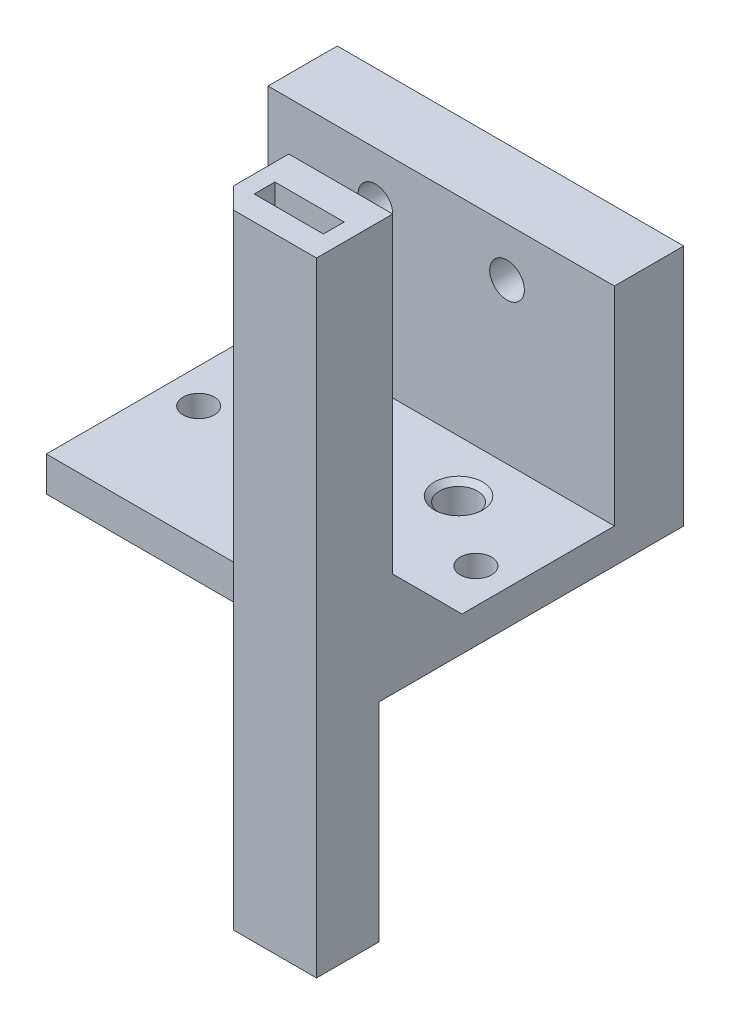
SolidWorks part; units mm, degrees
material "PET"
ref_plane "Front Plane" through (0, 0, 0) normal (0, 0, 1) x (1, 0, 0)
ref_plane "Top Plane" through (0, 0, 0) normal (0, 1, 0) x (1, 0, 0)
ref_plane "Right Plane" through (0, 0, 0) normal (1, 0, 0) x (0, 0, -1)
sketch "Sketch1" plane through (0, 0, 0) normal (0, 1, 0) x (1, 0, 0)
  line L0 (-30, 15) -> (30, 15) construction
  line L2 (-25, 0) -> (-25, 40)
  line L3 (-25, 40) -> (25, 40)
  line L4 (25, 0) -> (25, 40)
  line L5 (0, 0) -> (25, 40) construction
  line L6 (-25, 40) -> (0, 0) construction
  line L7 (-25, 22.5) -> (25, 22.5) construction
  line L8 (-25, 0) -> (-25, -2)
  line L11 (-25, -2) -> (25, -2)
  line L12 (25, -2) -> (25, 0)
  line L13 (-25, 0) -> (25, 0) construction
  line L14 (0, 0) -> (0, 27.8808) construction
  circle A0 centre (-10, 22.5) radius 2.75
  circle A1 centre (10, 22.5) radius 2.75
  circle A3 centre (-20, 15) radius 2.25
  circle A4 centre (20, 15) radius 2.25
  circle A6 centre (0, 6) radius 2.75
  point P0 (0, 0)
  dimension "D5" = 5.5
  dimension "D6" = 5.5
  dimension "D7" = 5.5
  dimension "D8" = 4.5
  dimension "D9" = 4.5
  dimension "D10" = 5
  dimension "D11" = 5
  dimension "D13" = 6
  dimension "D21" = 15
  dimension "D2" = 50
  dimension "D3" = 2
  dimension "D4" = 17.5
  dimension "D12" = 25
  dimension "D17" = 40
  dimension "D18" = 25
  dimension "D20" = 15
extrude "Boss-Extrude1" add sketch "Sketch1" along normal blind 5
sketch "Sketch3" plane through (0, 5, 0) normal (0, 1, 0) x (1, 0, 0)
  line L2 (-25, 40) -> (-25, 30)
  line L3 (-25, 30) -> (25, 30)
  line L5 (25, 40) -> (-25, 40)
  line L6 (25, 40) -> (25, 30)
  dimension "D2" = 10
extrude "Boss-Extrude3" add sketch "Sketch3" along normal blind 30
sketch "Sketch4" plane through (0, 0, -40) normal (0, 0, -1) x (-1, 0, 0)
  line L0 (-25, 0) -> (25, 0) construction
  line L2 (-9.5, 28) -> (9.5, 28) construction
  circle A0 centre (-9.5, 28) radius 2.5
  circle A1 centre (9.5, 28) radius 2.5
  dimension "D3" = 5
  dimension "D4" = 5
  dimension "D5" = 28
  dimension "D1" = 9.5
  dimension "D2" = 19
extrude "Cut-Extrude1" cut sketch "Sketch4" against normal through all
chamfer "Chamfer1" distance 0.75 angle 45 3 edges at (-10, 5, -19.75) (10, 5, -19.75) (0, 5, -3.25)
sketch "Sketch5" plane through (0, 0, 0) normal (0, -1, 0) x (1, 0, 0)
  line L0 (13, 13) -> (10, 10)
  line L1 (25, 2) -> (10, 2)
  line L2 (25, 2) -> (25, 13)
  line L3 (25, 13) -> (13, 13)
  line L6 (10, 2) -> (10, 10)
  line L7 (22.5, 9.5) -> (12.5, 9.5)
  line L8 (22.5, 9.5) -> (22.5, 6.5)
  line L9 (22.5, 6.5) -> (12.5, 6.5)
  line L10 (12.5, 9.5) -> (12.5, 6.5)
  dimension "D1" = 11
  dimension "D2" = 12
  dimension "D3" = 10
  dimension "D4" = 2.5
  dimension "D5" = 3
  dimension "D6" = 4.5
  dimension "D7" = 15
  dimension "D8" = 135
extrude "Boss-Extrude4" add sketch "Sketch5" along normal blind 30 and the other way blind 60
chamfer "Chamfer2" distance 10 angle 45 1 edges at (17.5, 5, 2)
chamfer "Chamfer3" distance 5 angle 45 2 edges at (10, 5, -3) (10, 2.5, 2)
sketch "Sketch7" plane through (25, 0, 0) normal (1, 0, 0) x (0, 0, -1)
  line L0 (-2, -30) -> (-13, -30) construction
  line L1 (-2, 0) -> (-4, 0)
  line L2 (-2, 0) -> (-2, -30)
  line L3 (-2, -30) -> (-4, -30)
  line L4 (-4, 0) -> (-4, -30)
  dimension "D1" = 2
extrude "Cut-Extrude2" cut sketch "Sketch7" against normal through all
